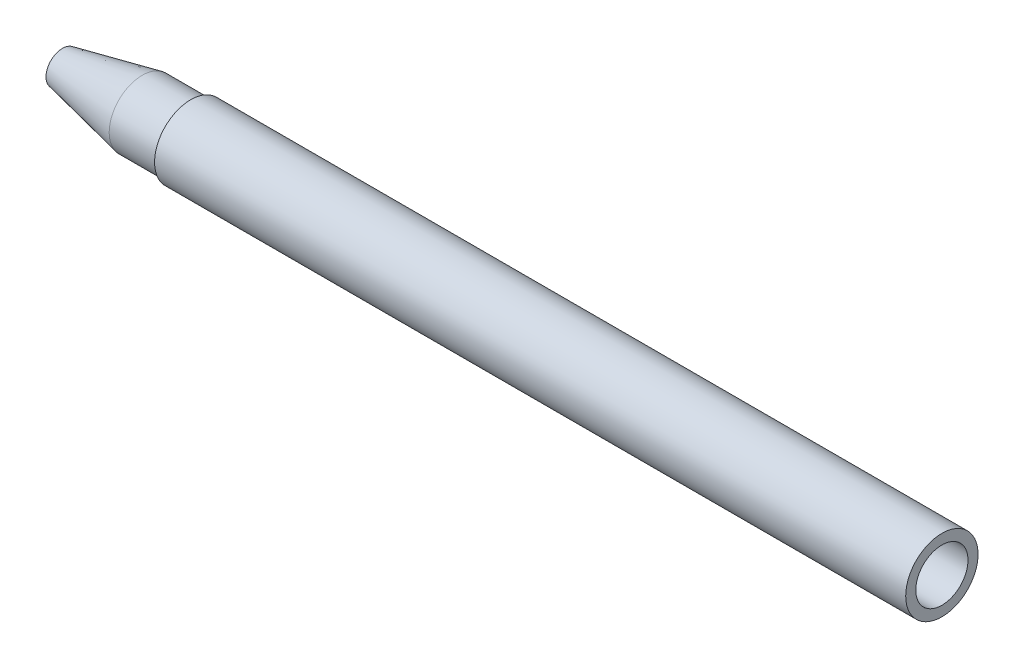
SolidWorks part; units mm, degrees
material "PP Film"
ref_plane "Front Plane" through (0, 0, 0) normal (0, 0, 1) x (1, 0, 0)
ref_plane "Top Plane" through (0, 0, 0) normal (0, 1, 0) x (1, 0, 0)
ref_plane "Right Plane" through (0, 0, 0) normal (1, 0, 0) x (0, 0, -1)
sketch "Sketch1" plane through (0, 0, 0) normal (0, 0, 1) x (1, 0, 0)
  line L0 (-51.9, 0) -> (51.9, 0)
  line L1 (51.9, 0) -> (51.9, -1.39)
  line L3 (-51.9, 0) -> (-51.9, -0.43)
  line L4 (-51.9, -0.43) -> (-58.6, -0.43)
  line L5 (-58.6, -0.43) -> (-69.63, -2.73)
  line L9 (-81.2361, -5) -> (54.8523, -5) construction
  line L10 (51.9, -1.39) -> (-58.6, -1.39)
  line L11 (-58.6, -1.39) -> (-69.63, -3.69)
  line L12 (-69.63, -3.69) -> (-69.63, -2.73)
  point P4 (0, 0)
  dimension "D1" = 1.39
  dimension "D2" = 103.8
  dimension "D3" = 0.43
  dimension "D4" = 6.7
  dimension "D5" = 11.03
  dimension "D6" = 2.3
  dimension "D7" = 5
revolve "Revolve1" add sketch "Sketch1" angle 360 about L9
